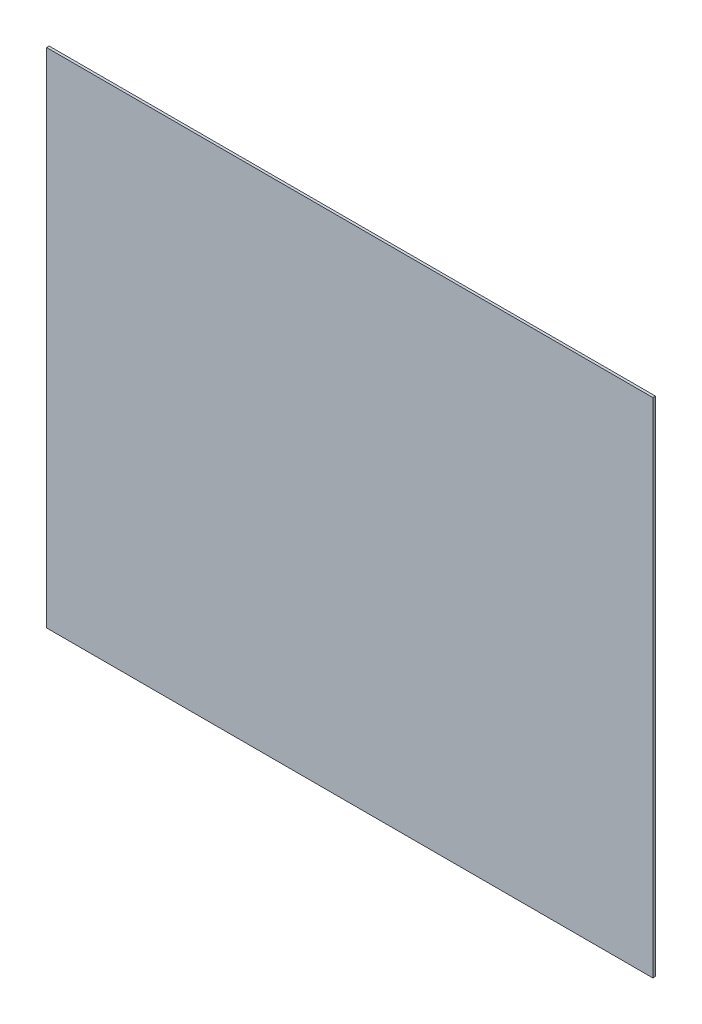
SolidWorks part; units mm, degrees
ref_plane "Front Plane" through (0, 0, 0) normal (0, 0, 1) x (1, 0, 0)
ref_plane "Top Plane" through (0, 0, 0) normal (0, 1, 0) x (1, 0, 0)
ref_plane "Right Plane" through (0, 0, 0) normal (1, 0, 0) x (0, 0, -1)
sketch "Sketch1" plane through (0, 0, 0) normal (0, 0, 1) x (1, 0, 0)
  line L1 (-371.475, -307.975) -> (371.475, -307.975)
  line L2 (-371.475, -307.975) -> (-371.475, 307.975)
  line L3 (-371.475, 307.975) -> (371.475, 307.975)
  line L4 (371.475, -307.975) -> (371.475, 307.975)
  line L5 (-371.475, -307.975) -> (371.475, 307.975) construction
  line L6 (-371.475, 307.975) -> (371.475, -307.975) construction
  point P0 (0, 0)
  dimension "D1" = 742.95
  dimension "D2" = 615.95
extrude "Boss-Extrude1" add sketch "Sketch1" along normal blind 3.175
